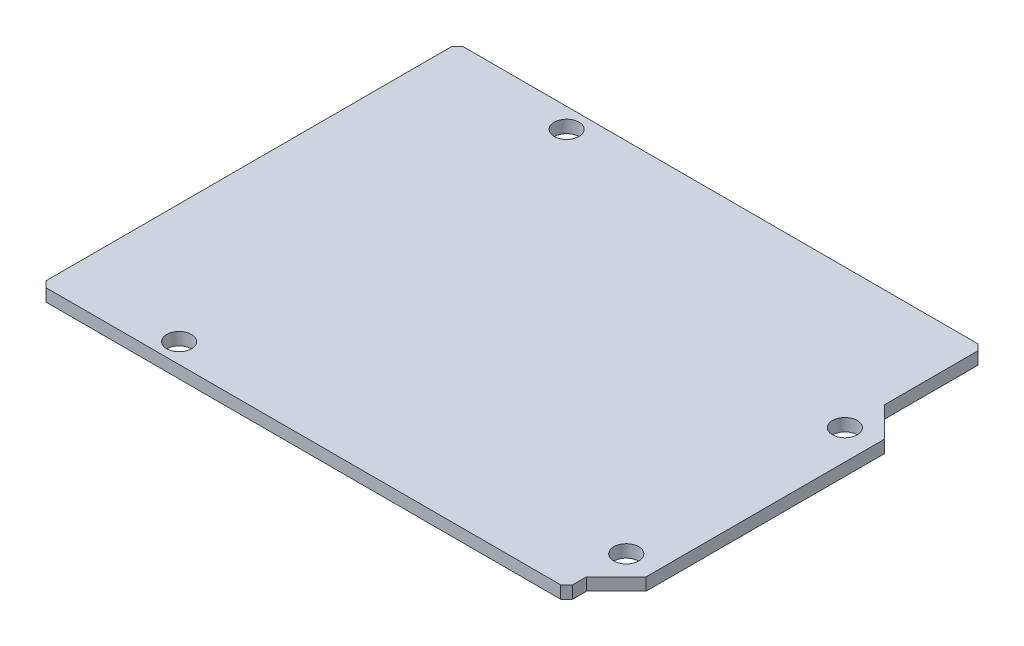
SolidWorks part; units mm, degrees
ref_plane "Front Plane" through (0, 0, 0) normal (0, 0, 1) x (1, 0, 0)
ref_plane "Top Plane" through (0, 0, 0) normal (0, 1, 0) x (1, 0, 0)
ref_plane "Right Plane" through (0, 0, 0) normal (1, 0, 0) x (0, 0, -1)
sketch "Sketch1" plane through (0, 0, 0) normal (0, 1, 0) x (1, 0, 0)
  line L0 (0, 0) -> (0, 53.34)
  line L1 (0, 53.34) -> (67.31, 53.34)
  line L2 (67.31, 53.34) -> (67.31, 40.64)
  line L3 (67.31, 40.64) -> (71.12, 36.83)
  line L4 (71.12, 36.83) -> (71.12, 6.35)
  line L6 (67.31, 0) -> (0, 0)
  line L7 (67.31, 0) -> (67.31, 2.54)
  line L8 (67.31, 2.54) -> (71.12, 6.35)
  line L9 (67.31, 33.2746) -> (67.31, 5.65) construction
  circle A0 centre (16.51, 50.8) radius 1.5875
  circle A1 centre (15.24, 2.54) radius 1.5875
  circle A2 centre (67.31, 35.56) radius 1.5875
  circle A3 centre (67.31, 7.62) radius 1.5875
  point P19 (20.5067, 49.6654)
  dimension "D6" = 3.175
  dimension "D1" = 67.31
  dimension "D2" = 53.34
  dimension "D3" = 71.12
  dimension "D4" = 135
  dimension "D5" = 135
  dimension "D7" = 2.54
  dimension "D8" = 15.24
  dimension "D9" = 7.62
  dimension "D10" = 27.94
  dimension "D11" = 40.64
  dimension "D12" = 2.54
  dimension "D13" = 1.27
  dimension "D14" = 15.24
extrude "Boss-Extrude1" add sketch "Sketch1" along normal blind 1.6002
chamfer "Chamfer1" distance 0.762 angle 45 4 edges at (0, 0.8001, -53.34) (0, 0.8001, 0) (67.31, 0.8001, -53.34) (67.31, 0.8001, 0)
